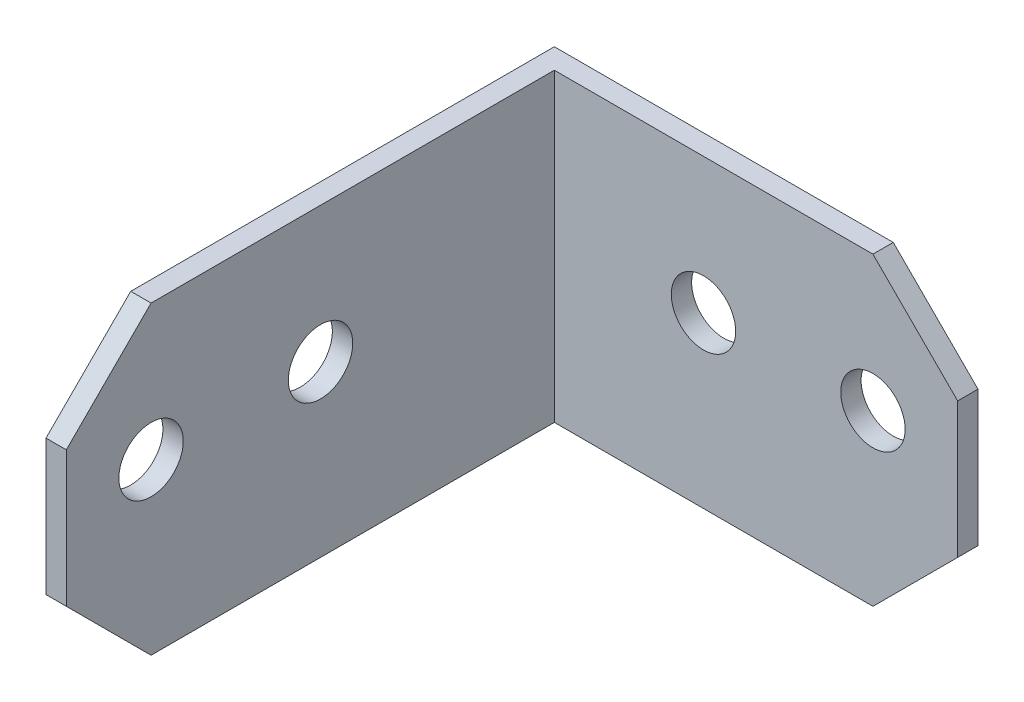
SolidWorks part; units mm, degrees
ref_plane "Front Plane" through (0, 0, 0) normal (0, 0, 1) x (1, 0, 0)
ref_plane "Top Plane" through (0, 0, 0) normal (0, 1, 0) x (1, 0, 0)
ref_plane "Right Plane" through (0, 0, 0) normal (1, 0, 0) x (0, 0, -1)
sketch "Sketch1" plane through (0, 0, 0) normal (0, 1, 0) x (1, 0, 0)
  line L0 (0, 0) -> (0, 38.1)
  line L1 (0, 38.1) -> (31.75, 38.1)
  line L2 (31.75, 38.1) -> (31.75, 36.576)
  line L3 (31.75, 36.576) -> (1.524, 36.576)
  line L4 (1.524, 36.576) -> (1.524, 0)
  line L5 (1.524, 0) -> (0, 0)
  dimension "D1" = 31.75
  dimension "D2" = 38.1
  dimension "D3" = 1.524
  dimension "D4" = 1.524
extrude "Boss-Extrude1" add sketch "Sketch1" along normal blind 22.86
sketch "Sketch2" plane through (1.524, 0, 0) normal (1, 0, 0) x (0, 0, -1)
  line L0 (0, 22.86) -> (36.576, 22.86) construction
  line L1 (38.1, 22.86) -> (38.1, 0) construction
  circle A0 centre (6.35, 12.7) radius 2.413
  circle A1 centre (19.05, 12.7) radius 2.413
  dimension "D1" = 4.826
  dimension "D2" = 4.826
  dimension "D3" = 10.16
  dimension "D4" = 12.7
  dimension "D5" = 10.16
  dimension "D6" = 19.05
sketch "Sketch3" plane through (0, 0, -36.576) normal (0, 0, 1) x (1, 0, 0)
  line L0 (1.524, 22.86) -> (31.75, 22.86) construction
  line L1 (0, 22.86) -> (0, 0) construction
  circle A0 centre (25.4, 12.7) radius 2.413
  circle A1 centre (12.7, 12.7) radius 2.413
  dimension "D1" = 4.826
  dimension "D2" = 4.826
  dimension "D3" = 10.16
  dimension "D4" = 10.16
  dimension "D5" = 12.7
  dimension "D6" = 12.7
extrude "Cut-Extrude1" cut sketch "Sketch2" against normal through all
extrude "Cut-Extrude2" cut sketch "Sketch3" against normal through all
chamfer "Chamfer1" distance 6.35 angle 45 4 edges at (0.762, 0, 0) (31.75, 0, -37.338) (0.762, 22.86, 0) (31.75, 22.86, -37.338)
